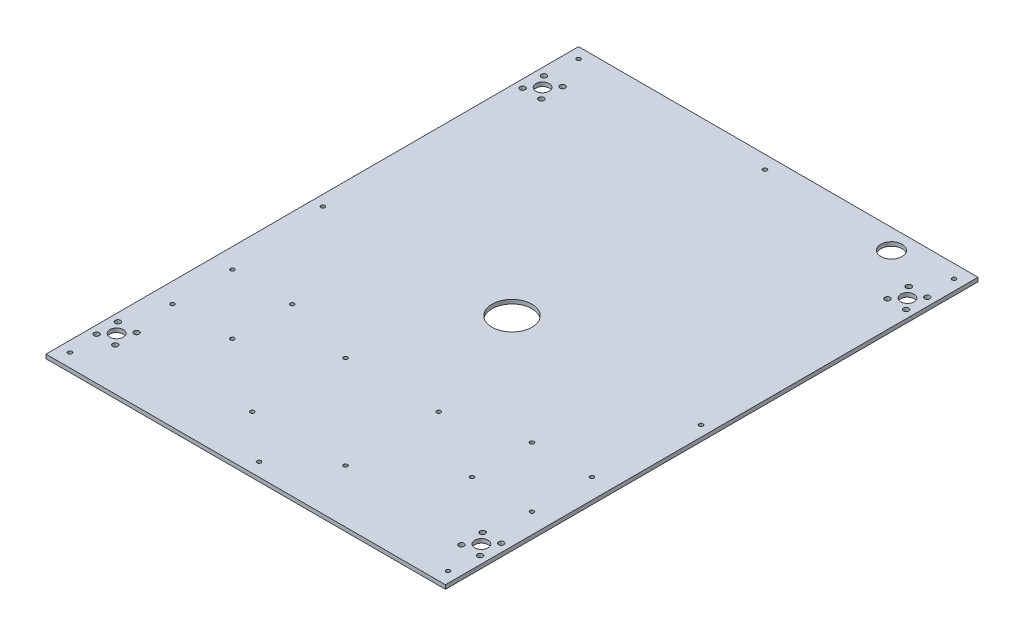
SolidWorks part; units mm, degrees
material "A-玻璃纤维"
ref_plane "前视基准面" through (0, 0, 0) normal (0, 0, 1) x (1, 0, 0)
ref_plane "上视基准面" through (0, 0, 0) normal (0, 1, 0) x (1, 0, 0)
ref_plane "右视基准面" through (0, 0, 0) normal (1, 0, 0) x (0, 0, -1)
sketch "草图1" plane through (0, 0, 0) normal (0, 1, 0) x (1, 0, 0)
  line L0 (0, 295.9627) -> (0, -253.3648) construction
  line L1 (-150, 200) -> (150, 200)
  line L2 (-150, 200) -> (-150, -200)
  line L3 (-150, -200) -> (150, -200)
  line L4 (150, 200) -> (150, -200)
  line L5 (-150, 200) -> (150, -200) construction
  line L6 (-150, -200) -> (150, 200) construction
  line L7 (-137, 310.1491) -> (-137, -253.3648) construction
  line L8 (137, 342.4725) -> (137, -253.3969) construction
  line L9 (-227.306, 0) -> (206.2046, 0) construction
  line L10 (-211.6958, 160) -> (161.4725, 160) construction
  circle A0 centre (-137, 160) radius 5
  circle A1 centre (137, 160) radius 5
  circle A2 centre (137, -160) radius 5
  circle A3 centre (-137, -160) radius 5
  circle A4 centre (-144, 168) radius 2
  circle A5 centre (-130, 168) radius 2
  circle A6 centre (-130, 152) radius 2
  circle A7 centre (-144, 152) radius 2
  circle A8 centre (130, 152) radius 2
  circle A9 centre (144, 152) radius 2
  circle A10 centre (130, 168) radius 2
  circle A11 centre (144, 168) radius 2
  circle A12 centre (144, -152) radius 2
  circle A13 centre (130, -152) radius 2
  circle A14 centre (144, -168) radius 2
  circle A15 centre (130, -168) radius 2
  circle A16 centre (-144, -152) radius 2
  circle A17 centre (-130, -152) radius 2
  circle A18 centre (-130, -168) radius 2
  circle A19 centre (-144, -168) radius 2
  point P0 (0, 0)
  dimension "D5" = 10
  dimension "D6" = 10
  dimension "D7" = 10
  dimension "D8" = 10
  dimension "D13" = 4
  dimension "D14" = 4
  dimension "D15" = 4
  dimension "D16" = 4
  dimension "D1" = 300
  dimension "D2" = 400
  dimension "D3" = 13
  dimension "D4" = 13
  dimension "D9" = 160
  dimension "D10" = 160
  dimension "D11" = 274
  dimension "D12" = 274
  dimension "D17" = 8
  dimension "D18" = 16
  dimension "D19" = 14
  dimension "D20" = 14
  dimension "D21" = 7
  dimension "D22" = 14
  dimension "D23" = 8
  dimension "D24" = 16
extrude "凸台-拉伸1" add sketch "草图1" along normal blind 3
sketch "草图2" plane through (0, 3, 0) normal (0, 1, 0) x (1, 0, 0)
  line L0 (-135, 218.997) -> (-135, -233.4303) construction
  line L1 (0, 223.3455) -> (0, -251.8689) construction
  line L2 (-150, 200) -> (-150, -200) construction
  line L3 (-112, 218.997) -> (-112, -233.4303) construction
  line L4 (-180.4529, 0) -> (164.3101, 0) construction
  line L5 (-135, 120) -> (-162.0238, 120) construction
  line L6 (-162.0238, 120) -> (-100.845, 120) construction
  circle A0 centre (-135, 130) radius 1.5
  circle A1 centre (-135, 110) radius 1.5
  circle A2 centre (-112, 120) radius 1.5
  circle A3 centre (112, 120) radius 1.5
  circle A4 centre (135, 110) radius 1.5
  circle A5 centre (135, 130) radius 1.5
  circle A6 centre (135, -110) radius 1.5
  circle A7 centre (135, -130) radius 1.5
  circle A8 centre (112, -120) radius 1.5
  circle A9 centre (-135, -110) radius 1.5
  circle A10 centre (-112, -120) radius 1.5
  circle A11 centre (-135, -130) radius 1.5
  dimension "D3" = 3
  dimension "D4" = 3
  dimension "D6" = 3
  dimension "D1" = 15
  dimension "D2" = 23
  dimension "D5" = 20
  dimension "D7" = 10
  dimension "D8" = 0
  dimension "D9" = 120
sketch "草图3" plane through (0, 3, 0) normal (0, 1, 0) x (1, 0, 0)
  line L0 (-201.5106, 0) -> (324.7484, 0) construction
  line L1 (-201.5106, 185) -> (260.3539, 185) construction
  line L2 (0, 219.5521) -> (0, -230.0995) construction
  line L3 (-201.5106, 162) -> (276.4525, 162) construction
  line L4 (150, 200) -> (-150, 200) construction
  line L5 (-90, 200) -> (-90, 138.098) construction
  circle A0 centre (-100, 185) radius 1.5
  circle A1 centre (-80, 185) radius 1.5
  circle A2 centre (90, 162) radius 1.5
  circle A3 centre (80, 185) radius 1.5
  circle A4 centre (-90, 162) radius 1.5
  circle A5 centre (100, 185) radius 1.5
  circle A6 centre (90, -162) radius 1.5
  circle A7 centre (100, -185) radius 1.5
  circle A8 centre (80, -185) radius 1.5
  circle A9 centre (-90, -162) radius 1.5
  circle A10 centre (-80, -185) radius 1.5
  circle A11 centre (-100, -185) radius 1.5
  dimension "D4" = 3
  dimension "D5" = 3
  dimension "D6" = 3
  dimension "D1" = 15
  dimension "D2" = 23
  dimension "D3" = 20
  dimension "D7" = 10
  dimension "D8" = 0
  dimension "D9" = 90
sketch "草图4" plane through (0, 3, 0) normal (0, 1, 0) x (1, 0, 0)
  line L0 (-180.4529, 0) -> (164.3101, 0) construction
  line L1 (0, 223.3455) -> (0, -251.8689) construction
  line L2 (-150, -200) -> (150, -200) construction
  line L3 (-150, 200) -> (-150, -200) construction
  line L5 (150, -200) -> (150, 200) construction
  line L8 (150, 200) -> (-150, 200) construction
  circle A0 centre (-142, -190) radius 1.5
  circle A1 centre (142, -190) radius 1.5
  circle A2 centre (142, 0) radius 1.5
  circle A3 centre (-142, 0) radius 1.5
  circle A4 centre (-142, 192) radius 1.5
  circle A5 centre (142, 190) radius 1.5
  circle A6 centre (0, 190) radius 1.5
  circle A7 centre (0, -190) radius 1.5
  dimension "D6" = 3
  dimension "D7" = 3
  dimension "D8" = 3
  dimension "D10" = 3
  dimension "D11" = 3
  dimension "D13" = 8
  dimension "D15" = 3
  dimension "D17" = 3
  dimension "D18" = 3
  dimension "D1" = 10
  dimension "D2" = 8
  dimension "D3" = 10
  dimension "D4" = 10
  dimension "D5" = 8
  dimension "D9" = 8
  dimension "D12" = 8
  dimension "D14" = 10
  dimension "D16" = 10
  dimension "D19" = 8
  dimension "D20" = 8
extrude "切除-拉伸1" cut sketch "草图4" against normal through all
sketch "草图5" plane through (0, 0, 0) normal (0, -1, 0) x (1, 0, 0)
  line L0 (-135, -218.997) -> (-135, 233.4303) construction
  line L1 (-150, 200) -> (150, 200) construction
  line L2 (-150, -200) -> (-150, 200) construction
  line L3 (0, 228.1448) -> (0, -220.8851) construction
  circle A0 centre (-135, 120) radius 1.5
  circle A1 centre (-90, 120) radius 1.5
  circle A2 centre (-135, 75) radius 1.5
  circle A3 centre (-90, 75) radius 1.5
  circle A4 centre (90, 75) radius 1.5
  circle A5 centre (135, 75) radius 1.5
  circle A6 centre (90, 120) radius 1.5
  circle A7 centre (135, 120) radius 1.5
  dimension "D1" = 3
  dimension "D3" = 3
  dimension "D7" = 3
  dimension "D8" = 3
  dimension "D9" = 60
  dimension "D2" = 80
  dimension "D4" = 45
  dimension "D5" = 45
  dimension "D6" = 45
  dimension "D10" = 60
extrude "切除-拉伸2" cut sketch "草图5" against normal blind 10
sketch "草图6" plane through (0, 0, 0) normal (0, -1, 0) x (1, 0, 0)
  line L0 (-234.4977, 125.6359) -> (312.7893, 125.6359) construction
  line L1 (0, -223.3455) -> (0, 251.8689) construction
  line L2 (-150, 200) -> (150, 200) construction
  circle A0 centre (-35, 160) radius 1.5
  circle A1 centre (35, 160) radius 1.5
  circle A2 centre (-35, 90) radius 1.5
  circle A3 centre (35, 90) radius 1.5
  dimension "D1" = 3
  dimension "D2" = 3
  dimension "D3" = 3
  dimension "D4" = 3
  dimension "D5" = 70
  dimension "D6" = 70
  dimension "D7" = 70
  dimension "D8" = 35
  dimension "D9" = 40
  dimension "D10" = 70
  dimension "D11" = 35
  dimension "D12" = 35
extrude "切除-拉伸3" cut sketch "草图6" against normal through all
sketch "草图7" plane through (0, 0, 0) normal (0, -1, 0) x (1, 0, 0)
  circle A0 centre (0, 0) radius 15
  dimension "D1" = 30
extrude "切除-拉伸4" cut sketch "草图7" against normal through all
sketch "草图8" plane through (0, 3, 0) normal (0, 1, 0) x (1, 0, 0)
  circle A0 centre (100, 185) radius 8
  dimension "D1" = 16
extrude "切除-拉伸5" cut sketch "草图8" against normal blind 10
